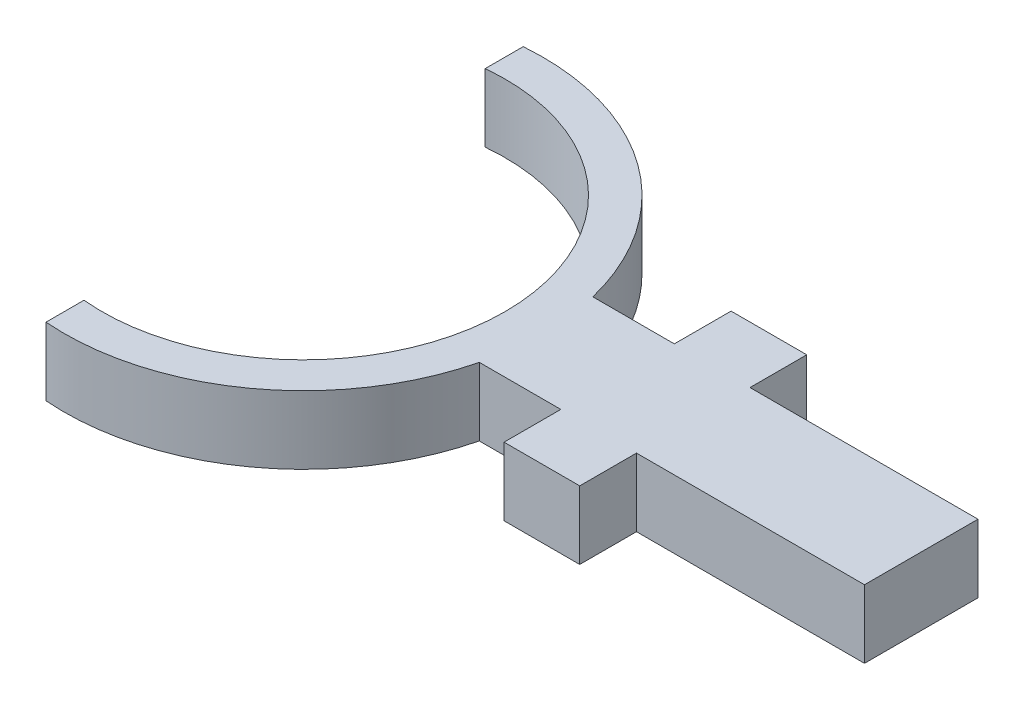
SolidWorks part; units mm, degrees
ref_plane "前视基准面" through (0, 0, 0) normal (0, 0, 1) x (1, 0, 0)
ref_plane "上视基准面" through (0, 0, 0) normal (0, 1, 0) x (1, 0, 0)
ref_plane "右视基准面" through (0, 0, 0) normal (1, 0, 0) x (0, 0, -1)
other "Configuration Table"
sketch "草图1" plane through (0, 0, 0) normal (0, 1, 0) x (1, 0, 0)
  circle A0 centre (0, 0) radius 5.3262
  circle A1 centre (0, 0) radius 6.3262
  circle A2 centre (0, 0) radius 5.2262 construction
  dimension "D1" = 0.1
  dimension "D2" = 1
extrude "凸台-拉伸1" add sketch "草图1" along normal blind 1.8
ref_plane "基准面1" through (6.3262, 0, 0) normal (1, 0, 0) x (0, 0, -1)
sketch "草图2" plane through (6.3262, 0, 0) normal (1, 0, 0) x (0, 0, -1)
  line L0 (6.3262, 1.8) -> (-6.3262, 1.8) construction
  line L1 (-1.5, 1.8) -> (1.5, 1.8)
  line L2 (-1.5, 1.8) -> (-1.5, 0)
  line L3 (-1.5, 0) -> (1.5, 0)
  line L4 (1.5, 1.8) -> (1.5, 0)
  line L5 (0, 0) -> (0, 0.8122) construction
  dimension "D1" = 3
extrude "凸台-拉伸2" add sketch "草图2" along normal blind 10 and the other way blind 0.5
sketch "草图3" plane through (0, 1.8, 0) normal (0, 1, 0) x (1, 0, 0)
  line L0 (16.3262, 1.5) -> (16.3262, -1.5) construction
  line L1 (-6.962, 7.5396) -> (-0.5, 7.5396)
  line L2 (-6.962, 7.5396) -> (-6.962, -7.4604)
  line L3 (-6.962, -7.4604) -> (-0.5, -7.4604)
  line L4 (-0.5, 7.5396) -> (-0.5, -7.4604)
  line L5 (16.3262, 1.5) -> (16.3262, -1.5) construction
  dimension "D1" = 0.5
  dimension "D2" = 15
extrude "切除-拉伸1" cut sketch "草图3" against normal up to next
sketch "草图4" plane through (0, 1.8, 0) normal (0, 1, 0) x (1, 0, 0)
  line L0 (16.3262, 0) -> (12.6222, 0) construction
  line L1 (10.3, 3) -> (8.3, 3)
  line L2 (10.3, 3) -> (10.3, -3)
  line L3 (10.3, -3) -> (8.3, -3)
  line L4 (8.3, 3) -> (8.3, -3)
  line L5 (16.3262, 1.5) -> (16.3262, -1.5) construction
  circle A0 centre (0, 0) radius 5.2262 construction
  dimension "D1" = 10.3
  dimension "D2" = 6
  dimension "D3" = 2
extrude "凸台-拉伸3" add sketch "草图4" along normal up to surface (1.8 mm away)
